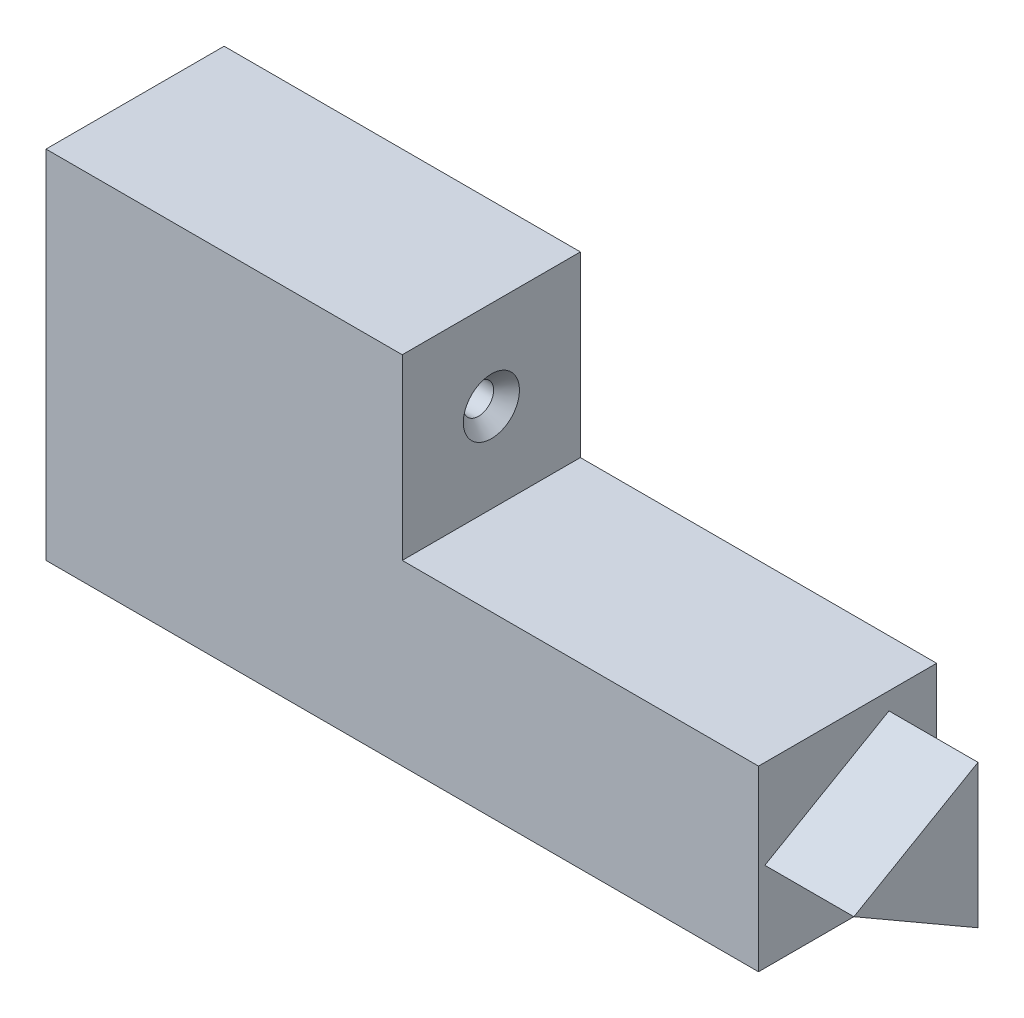
SolidWorks part; units mm, degrees
ref_plane "Спереди" through (0, 0, 0) normal (0, 0, 1) x (1, 0, 0)
ref_plane "Сверху" through (0, 0, 0) normal (0, 1, 0) x (1, 0, 0)
ref_plane "Справа" through (0, 0, 0) normal (1, 0, 0) x (0, 0, -1)
sketch "Эскиз1" plane through (0, 0, 0) normal (1, 0, 0) x (0, 0, -1)
  line L1 (-37.7241, -17.639) -> (-17.7241, -17.639)
  line L2 (-37.7241, -17.639) -> (-37.7241, 22.361)
  line L3 (-37.7241, 22.361) -> (-17.7241, 22.361)
  line L4 (-17.7241, -17.639) -> (-17.7241, 22.361)
  dimension "D1" = 40
  dimension "D2" = 20
extrude "Бобышка-Вытянуть1" add sketch "Эскиз1" along normal blind 40
sketch "Эскиз2" plane through (40, 0, 0) normal (1, 0, 0) x (0, 0, -1)
  line L0 (-27.7241, 22.361) -> (-27.7241, -9.226) construction
  line L1 (-17.7241, 22.361) -> (-37.7241, 22.361) construction
  line L3 (-17.7241, -17.639) -> (-17.7241, 22.361) construction
  line L4 (-46.9913, 12.361) -> (-2.5903, 12.361) construction
  line L6 (-37.7241, 22.361) -> (-17.7241, 22.361)
  line L7 (-37.7241, 22.361) -> (-37.7241, 12.361)
  line L8 (-37.7241, 12.361) -> (-17.7241, 12.361)
  line L9 (-17.7241, 22.361) -> (-17.7241, 12.361)
  dimension "D1" = 10
  dimension "D2" = 20
sketch "Эскиз16" plane through (40, 0, 0) normal (1, 0, 0) x (0, 0, -1)
  line L0 (-17.7241, -17.639) -> (-17.7241, 22.361) construction
  line L1 (-37.7241, -17.639) -> (-17.7241, -17.639)
  line L2 (-37.7241, -17.639) -> (-37.7241, 2.361)
  line L3 (-37.7241, 2.361) -> (-17.7241, 2.361)
  line L4 (-17.7241, -17.639) -> (-17.7241, 2.361)
extrude "Бобышка-Вытянуть2" add sketch "Эскиз16" along normal blind 40
hole_wizard "Зенковка для винта с полупотайной головкой M31" positions "Эскиз17" profile "Эскиз18" countersink size "M3" standard "ISO" end condition through all
sketch "Эскиз17" plane through (40, 0, 0) normal (1, 0, 0) x (0, 0, -1)
  point P0 (-27.7179, 12.3441)
sketch "Эскиз18" plane through (40, 12.3441, 27.7179) normal (0, 1, 0) x (0, 0, -1)
  line L0 (0, 0) -> (0, 40)
  line L1 (0, 40) -> (1.7, 40)
  line L2 (1.7, 40) -> (1.7, 1.45)
  line L3 (1.7, 1.45) -> (3.15, 0)
  line L5 (3.15, 0) -> (0, 0)
  line L6 (-1.7, 1.45) -> (-3.15, 0) construction
  line L11 (0, -6.35) -> (0, 107.95) construction
  dimension "Диаметр сквозного отверстия" = 3.4
  dimension "Глубина сквозного отверстия" = 40
  dimension "Диаметр передней зенковки" = 6.3
  dimension "Угол передней зенковки" = 90
sketch "Эскиз19" plane through (80, 0, 0) normal (1, 0, 0) x (0, 0, -1)
  line L0 (-27.7241, 2.361) -> (-27.7241, -17.639) construction
  line L1 (-17.7241, 2.361) -> (-37.7241, 2.361) construction
  line L2 (-37.7241, -17.639) -> (-17.7241, -17.639) construction
  line L3 (-37.7241, -7.639) -> (-17.7241, -7.639) construction
  line L4 (-37.7241, 2.361) -> (-37.7241, -17.639) construction
  line L5 (-17.7241, -17.639) -> (-17.7241, 2.361) construction
  line L7 (-37.013, -7.639) -> (-23.0797, -15.6835)
  line L8 (-23.0797, -15.6835) -> (-23.0797, 0.4054)
  line L9 (-23.0797, 0.4054) -> (-37.013, -7.639)
  circle A0 centre (-27.7241, -7.639) radius 4.6445 construction
extrude "Бобышка-Вытянуть3" add sketch "Эскиз19" along normal blind 10
